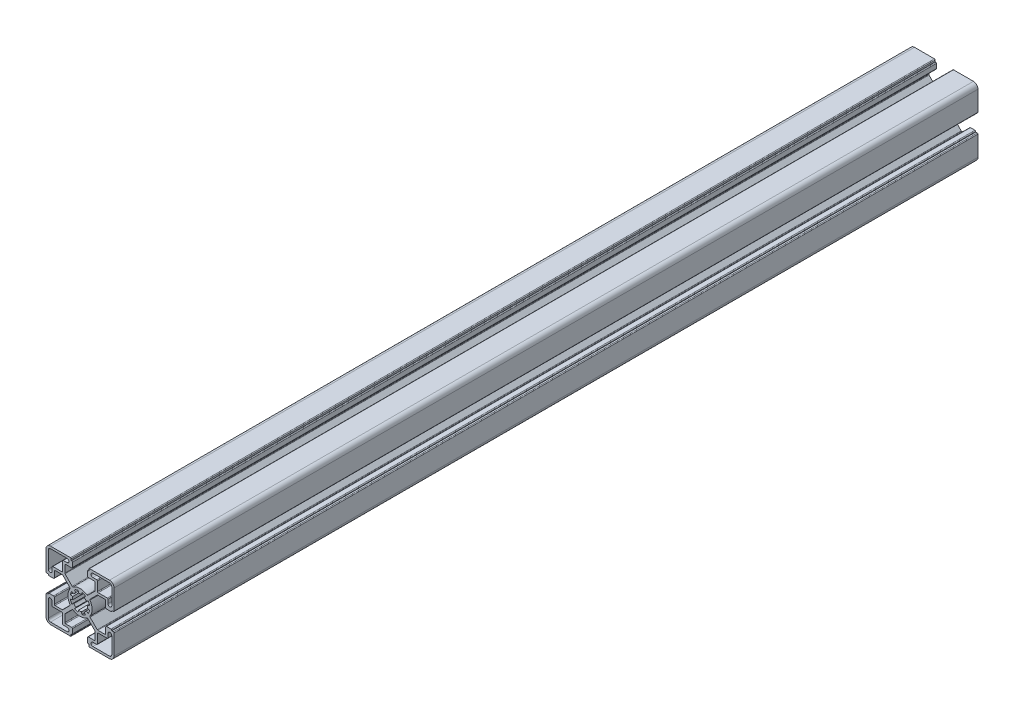
SolidWorks part; units mm, degrees
material "6063-O"
ref_plane "Front Plane" through (0, 0, 0) normal (0, 0, 1) x (1, 0, 0)
ref_plane "Top Plane" through (0, 0, 0) normal (0, 1, 0) x (1, 0, 0)
ref_plane "Right Plane" through (0, 0, 0) normal (1, 0, 0) x (0, 0, -1)
sketch "Sketch1" plane through (0, 0, 0) normal (0, 0, 1) x (1, 0, 0)
  line L0 (0, 22.5) -> (0, -22.5) construction
  line L1 (22.5, 0) -> (-22.5, 0) construction
  line L2 (-5.8, 22.5) -> (5.8, 22.5) construction
  line L3 (-5, 21) -> (5, 21) construction
  line L4 (-10.05, 10.05) -> (10.05, 10.05) construction
  line L5 (0, 0) -> (-10.05, 10.05) construction
  circle A0 centre (0, 0) radius 5 construction
  point P4 (0, 0)
  point P8 (0, 0)
  point P10 (0, 8)
  point P14 (0, 22.5)
  point P17 (0, 21)
  point P19 (0, 10.05)
sketch "Sketch2" plane through (0, 0, 0) normal (1, 0, 0) x (0, 0, -1)
  line L0 (152.4, 0) -> (-152.4, 0) construction
  point P4 (0, 0)
  dimension "D1" = 304.8
sketch "Sketch3" plane through (0, 0, 0) normal (0, 0, 1) x (1, 0, 0)
  line L5 (-21, 8.5375) -> (-21, 19.5)
  line L9 (0, 0) -> (-22.5, 22.5) construction
  line L10 (-11.55, -10.05) -> (-6.3569, -4.8569)
  line L11 (-19.5, 21) -> (-8.5375, 21)
  line L38 (-5.8, 22.5) -> (-5.8, 21)
  line L46 (-5.8, 21) -> (-5, 21)
  line L62 (-5, 21) -> (-5, 17.025)
  line L74 (-5, 17.025) -> (-10.05, 17.025)
  line L76 (-10.05, 17.025) -> (-10.05, 11.55)
  line L77 (-10.05, 11.55) -> (-4.8569, 6.3569)
  line L78 (-18.525, 8.5375) -> (-18.525, 11.55)
  line L79 (-10.05, 17.025) -> (-10.05, 22.5) construction
  line L80 (0, 22.5) -> (0, -22.5) construction
  line L81 (-5.8, 22.5) -> (5.8, 22.5) construction
  line L82 (10.05, 11.55) -> (4.8569, 6.3569)
  line L83 (10.05, 17.025) -> (10.05, 11.55)
  line L84 (5, 17.025) -> (10.05, 17.025)
  line L85 (5, 21) -> (5, 17.025)
  line L86 (5.8, 21) -> (5, 21)
  line L87 (5.8, 22.5) -> (5.8, 21)
  line L88 (-22.5, -5.8) -> (-21, -5.8)
  line L89 (-21, -5.8) -> (-21, -5)
  line L90 (-21, -5) -> (-17.025, -5)
  line L91 (-17.025, -5) -> (-17.025, -10.05)
  line L92 (-17.025, -10.05) -> (-11.55, -10.05)
  line L93 (-11.55, -10.05) -> (-6.3569, -4.8569)
  line L94 (-11.55, 10.05) -> (-6.3569, 4.8569)
  line L95 (-17.025, 10.05) -> (-11.55, 10.05)
  line L96 (-17.025, 5) -> (-17.025, 10.05)
  line L97 (-21, 5) -> (-17.025, 5)
  line L98 (-21, 5.8) -> (-21, 5)
  line L99 (-22.5, 5.8) -> (-21, 5.8)
  line L100 (-22.5, 5.8) -> (-22.5, 19.5)
  line L101 (-19.5, 22.5) -> (-5.8, 22.5)
  line L102 (-18.525, 11.55) -> (-11.55, 11.55)
  line L103 (-8.5375, 18.525) -> (-11.55, 18.525)
  line L104 (-11.55, 18.525) -> (-11.55, 11.55)
  line L108 (5.8, -22.5) -> (5.8, -21)
  line L113 (5.8, -21) -> (5, -21)
  line L117 (5.8, 22.5) -> (19.5, 22.5)
  line L118 (22.5, 19.5) -> (22.5, 5.8)
  line L119 (19.5, -22.5) -> (5.8, -22.5)
  line L120 (0, 0) -> (22.5, 0) construction
  line L121 (-22.5, -19.5) -> (-22.5, -5.8)
  line L136 (5, -21) -> (5, -17.025)
  line L137 (5, -17.025) -> (10.05, -17.025)
  line L138 (10.05, -17.025) -> (10.05, -11.55)
  line L139 (10.05, -11.55) -> (4.8569, -6.3569)
  line L140 (-10.05, -11.55) -> (-4.8569, -6.3569)
  line L141 (-10.05, -17.025) -> (-10.05, -11.55)
  line L142 (-5, -17.025) -> (-10.05, -17.025)
  line L143 (-5, -21) -> (-5, -17.025)
  line L144 (-5.8, -21) -> (-5, -21)
  line L145 (-5.8, -22.5) -> (-5.8, -21)
  line L146 (-5.8, -22.5) -> (-19.5, -22.5)
  line L147 (22.5, 5.8) -> (21, 5.8)
  line L148 (21, 5.8) -> (21, 5)
  line L149 (21, 5) -> (17.025, 5)
  line L150 (17.025, 5) -> (17.025, 10.05)
  line L151 (17.025, 10.05) -> (11.55, 10.05)
  line L152 (11.55, 10.05) -> (6.3569, 4.8569)
  line L153 (11.55, -10.05) -> (6.3569, -4.8569)
  line L154 (17.025, -10.05) -> (11.55, -10.05)
  line L155 (17.025, -5) -> (17.025, -10.05)
  line L156 (21, -5) -> (17.025, -5)
  line L157 (21, -5.8) -> (21, -5)
  line L158 (22.5, -5.8) -> (21, -5.8)
  line L159 (11.55, -10.05) -> (6.3569, -4.8569)
  line L160 (22.5, -5.8) -> (22.5, -19.5)
  line L161 (8.5375, 21) -> (19.5, 21)
  line L162 (21, 19.5) -> (21, 8.5375)
  line L163 (8.5375, 18.525) -> (11.55, 18.525)
  line L164 (11.55, 18.525) -> (11.55, 11.55)
  line L165 (18.525, 8.5375) -> (18.525, 11.55)
  line L166 (18.525, 11.55) -> (11.55, 11.55)
  line L167 (21, -8.5375) -> (21, -19.5)
  line L168 (19.5, -21) -> (8.5375, -21)
  line L169 (18.525, -8.5375) -> (18.525, -11.55)
  line L170 (18.525, -11.55) -> (11.55, -11.55)
  line L171 (8.5375, -18.525) -> (11.55, -18.525)
  line L172 (11.55, -18.525) -> (11.55, -11.55)
  line L173 (-8.5375, -21) -> (-19.5, -21)
  line L174 (-21, -19.5) -> (-21, -8.5375)
  line L175 (-8.5375, -18.525) -> (-11.55, -18.525)
  line L176 (-11.55, -18.525) -> (-11.55, -11.55)
  line L177 (-18.525, -8.5375) -> (-18.525, -11.55)
  line L178 (-18.525, -11.55) -> (-11.55, -11.55)
  line L179 (0, 0) -> (-11.55, 11.55) construction
  line L180 (0, 0) -> (11.55, 11.55) construction
  arc A2 (-21, 19.5) -> (-19.5, 21) centre (-19.5, 19.5) cw
  arc A73 (-4.8569, 6.3569) -> (4.8569, 6.3569) centre (0, 0) cw
  arc A74 (-6.3569, 4.8569) -> (-6.3569, -4.8569) centre (0, 0) ccw
  arc A75 (-19.5, 22.5) -> (-22.5, 19.5) centre (-19.5, 19.5) ccw
  arc A76 (-21, 8.5375) -> (-18.525, 8.5375) centre (-19.7625, 8.5375) ccw
  arc A77 (-8.5375, 21) -> (-8.5375, 18.525) centre (-8.5375, 19.7625) cw
  arc A80 (19.5, 22.5) -> (22.5, 19.5) centre (19.5, 19.5) cw
  arc A81 (22.5, -19.5) -> (19.5, -22.5) centre (19.5, -19.5) cw
  arc A82 (-19.5, -22.5) -> (-22.5, -19.5) centre (-19.5, -19.5) cw
  circle A88 centre (0, 0) radius 5 construction
  circle A89 centre (0, 0) radius 5
  arc A90 (-4.8569, -6.3569) -> (4.8569, -6.3569) centre (0, 0) ccw
  arc A91 (19.5, 21) -> (21, 19.5) centre (19.5, 19.5) cw
  arc A92 (6.3569, 4.8569) -> (6.3569, -4.8569) centre (0, 0) cw
  arc A93 (8.5375, 21) -> (8.5375, 18.525) centre (8.5375, 19.7625) ccw
  arc A94 (21, 8.5375) -> (18.525, 8.5375) centre (19.7625, 8.5375) cw
  arc A95 (21, -19.5) -> (19.5, -21) centre (19.5, -19.5) cw
  arc A96 (21, -8.5375) -> (18.525, -8.5375) centre (19.7625, -8.5375) ccw
  arc A97 (8.5375, -21) -> (8.5375, -18.525) centre (8.5375, -19.7625) cw
  arc A98 (-19.5, -21) -> (-21, -19.5) centre (-19.5, -19.5) cw
  arc A99 (-8.5375, -21) -> (-8.5375, -18.525) centre (-8.5375, -19.7625) ccw
  arc A100 (-21, -8.5375) -> (-18.525, -8.5375) centre (-19.7625, -8.5375) cw
  point P54 (-14.2875, 10.05)
  dimension "D2" = 3
  dimension "D3" = 1.5
  dimension "D4" = 1.5
  dimension "D5" = 1.5
  dimension "D6" = 90
  dimension "D1" = 4
extrude "Boss-Extrude1" add sketch "Sketch3" along normal up to vertex (152.4 mm away) and the other way up to vertex (152.4 mm away) contours A92 L152 L151 L150 L149 L148 L147 L118 A80 L117 L87 L86 L85 L84 L83 L82 A73 L77 L76 L74 L62 L46 L38 L101 A75 L100 L99 L98 L97 L96 L95 L94 A74 L10 L92 L91 L90 L89 L88 L121 A82 L146 L145 L144 L143 L142 L141 L140 A90 L139 L138 up to point (0, 0, 152.4) other way up to point (0, 0, -152.4)
fillet "Fillet1" radius 0.5 58 edges at (5, 21, 0) (5.8, 22.5, 0) (-5.8, 22.5, 0) (-5, 21, 0) (-10.05, 17.025, 0) (-5, 17.025, 0) (5, 17.025, 0) (-22.5, -5.8, 0) (-21, -5, 0) (-17.025, -5, 0) (-17.025, -10.05, 0) (-11.55, -10.05, 0) (-6.3569, -4.8569, 0) (-6.3569, 4.8569, 0) (-11.55, 10.05, 0) (-17.025, 10.05, 0) (-17.025, 5, 0) (-22.5, 5.8, 0) (-21, 5, 0) (-18.525, 11.55, 0) (-11.55, 11.55, 0) (-11.55, 18.525, 0) (4.8569, 6.3569, 0) (-4.8569, 6.3569, 0) (-10.05, 11.55, 0) (10.05, 17.025, 0) (10.05, 11.55, 0) (22.5, -5.8, 0) (21, -5, 0) (17.025, -5, 0) (17.025, -10.05, 0) (6.3569, 4.8569, 0) (11.55, 10.05, 0) (22.5, 5.8, 0) (21, 5, 0) (17.025, 5, 0) (4.8569, -6.3569, 0) (11.55, -11.55, 0) (-11.55, -11.55, 0) (18.525, -11.55, 0) (11.55, -18.525, 0) (10.05, -17.025, 0) (5, -17.025, 0) (5, -21, 0) (5.8, -22.5, 0) (-5.8, -22.5, 0) (-5, -21, 0) (-5, -17.025, 0) (-10.05, -17.025, 0) (-11.55, -18.525, 0) (11.55, 18.525, 0) (18.525, 11.55, 0) (11.55, 11.55, 0) (11.55, -10.05, 0) (6.3569, -4.8569, 0) (-4.8569, -6.3569, 0) (10.05, -11.55, 0) (-10.05, -11.55, 0)
sketch "Sketch4" plane through (0, 0, 152.4) normal (0, 0, 1) x (1, 0, 0)
  line L0 (-1.2681, 6.3751) -> (-0.9755, 4.9039)
  line L1 (0, 0) -> (0, 8) construction
  line L2 (-3.6112, 5.4046) -> (-2.7779, 4.1573)
  line L3 (1.2681, 6.3751) -> (0.9755, 4.9039)
  line L4 (3.6112, 5.4046) -> (2.7779, 4.1573)
  line L5 (5.4046, 3.6112) -> (4.1573, 2.7779)
  line L6 (6.3751, 1.2681) -> (4.9039, 0.9755)
  line L7 (6.3751, -1.2681) -> (4.9039, -0.9755)
  line L8 (5.4046, -3.6112) -> (4.1573, -2.7779)
  line L9 (3.6112, -5.4046) -> (2.7779, -4.1573)
  line L10 (1.2681, -6.3751) -> (0.9755, -4.9039)
  line L11 (-1.2681, -6.3751) -> (-0.9755, -4.9039)
  line L12 (-3.6112, -5.4046) -> (-2.7779, -4.1573)
  line L13 (-5.4046, -3.6112) -> (-4.1573, -2.7779)
  line L14 (-6.3751, -1.2681) -> (-4.9039, -0.9755)
  line L15 (-6.3751, 1.2681) -> (-4.9039, 0.9755)
  line L16 (-5.4046, 3.6112) -> (-4.1573, 2.7779)
  line L17 (0, 0) -> (-0.9755, 4.9039) construction
  line L18 (0, 0) -> (2.7779, 4.1573) construction
  arc A0 (-1.2681, 6.3751) -> (-3.6112, 5.4046) centre (0, 0) ccw
  circle A1 centre (0, 0) radius 5 construction
  arc A2 (-0.9755, 4.9039) -> (-2.7779, 4.1573) centre (0, 0) ccw
  arc A4 (2.7779, 4.1573) -> (0.9755, 4.9039) centre (0, 0) ccw
  arc A5 (3.6112, 5.4046) -> (1.2681, 6.3751) centre (0, 0) ccw
  arc A6 (4.9039, 0.9755) -> (4.1573, 2.7779) centre (0, 0) ccw
  arc A7 (6.3751, 1.2681) -> (5.4046, 3.6112) centre (0, 0) ccw
  arc A8 (4.1573, -2.7779) -> (4.9039, -0.9755) centre (0, 0) ccw
  arc A9 (5.4046, -3.6112) -> (6.3751, -1.2681) centre (0, 0) ccw
  arc A10 (0.9755, -4.9039) -> (2.7779, -4.1573) centre (0, 0) ccw
  arc A11 (1.2681, -6.3751) -> (3.6112, -5.4046) centre (0, 0) ccw
  arc A12 (-2.7779, -4.1573) -> (-0.9755, -4.9039) centre (0, 0) ccw
  arc A13 (-3.6112, -5.4046) -> (-1.2681, -6.3751) centre (0, 0) ccw
  arc A14 (-4.9039, -0.9755) -> (-4.1573, -2.7779) centre (0, 0) ccw
  arc A15 (-6.3751, -1.2681) -> (-5.4046, -3.6112) centre (0, 0) ccw
  arc A16 (-4.1573, 2.7779) -> (-4.9039, 0.9755) centre (0, 0) ccw
  arc A17 (-5.4046, 3.6112) -> (-6.3751, 1.2681) centre (0, 0) ccw
  dimension "D1" = 1.5
  dimension "D2" = 22.5
  dimension "D5" = 45
  dimension "D4" = 8
extrude "Cut-Extrude1" cut sketch "Sketch4" against normal through all
sketch "Sketch5" plane through (0, 0, 152.4) normal (0, 0, 1) x (1, 0, 0)
  line L6 (-11.55, -18.025) -> (-11.55, -12.05)
  line L7 (-8.5375, -18.525) -> (-11.05, -18.525)
  line L8 (-19.5, -21) -> (-8.5375, -21)
  line L9 (-21, -8.5375) -> (-21, -19.5)
  line L10 (-18.525, -11.55) -> (-18.525, -8.5375)
  line L11 (-12.05, -11.55) -> (-18.525, -11.55)
  line L12 (-11.55, -18.025) -> (-11.55, -12.05)
  line L13 (-8.5375, -18.525) -> (-11.05, -18.525)
  line L14 (-19.5, -21) -> (-8.5375, -21)
  line L15 (-21, -8.5375) -> (-21, -19.5)
  line L16 (-0.9755, 4.9039) -> (-1.2681, 6.3751)
  line L17 (1.2681, 6.3751) -> (0.9755, 4.9039)
  line L18 (2.7779, 4.1573) -> (3.6112, 5.4046)
  line L19 (5.4046, 3.6112) -> (4.1573, 2.7779)
  line L20 (4.9039, 0.9755) -> (6.3751, 1.2681)
  line L21 (6.3751, -1.2681) -> (4.9039, -0.9755)
  line L22 (4.1573, -2.7779) -> (5.4046, -3.6112)
  line L23 (3.6112, -5.4046) -> (2.7779, -4.1573)
  line L24 (0.9755, -4.9039) -> (1.2681, -6.3751)
  line L25 (-1.2681, -6.3751) -> (-0.9755, -4.9039)
  line L26 (-2.7779, -4.1573) -> (-3.6112, -5.4046)
  line L27 (-5.4046, -3.6112) -> (-4.1573, -2.7779)
  line L28 (-4.9039, -0.9755) -> (-6.3751, -1.2681)
  line L29 (-6.3751, 1.2681) -> (-4.9039, 0.9755)
  line L30 (-4.1573, 2.7779) -> (-5.4046, 3.6112)
  line L31 (-3.6112, 5.4046) -> (-2.7779, 4.1573)
  line L32 (-0.9755, 4.9039) -> (-1.2681, 6.3751)
  line L33 (1.2681, 6.3751) -> (0.9755, 4.9039)
  line L34 (2.7779, 4.1573) -> (3.6112, 5.4046)
  line L35 (5.4046, 3.6112) -> (4.1573, 2.7779)
  line L36 (4.9039, 0.9755) -> (6.3751, 1.2681)
  line L37 (6.3751, -1.2681) -> (4.9039, -0.9755)
  line L38 (4.1573, -2.7779) -> (5.4046, -3.6112)
  line L39 (3.6112, -5.4046) -> (2.7779, -4.1573)
  line L40 (0.9755, -4.9039) -> (1.2681, -6.3751)
  line L41 (-1.2681, -6.3751) -> (-0.9755, -4.9039)
  line L42 (-2.7779, -4.1573) -> (-3.6112, -5.4046)
  line L43 (-5.4046, -3.6112) -> (-4.1573, -2.7779)
  line L44 (-4.9039, -0.9755) -> (-6.3751, -1.2681)
  line L45 (-6.3751, 1.2681) -> (-4.9039, 0.9755)
  line L46 (-4.1573, 2.7779) -> (-5.4046, 3.6112)
  line L47 (-3.6112, 5.4046) -> (-2.7779, 4.1573)
  line L48 (-18.525, -11.55) -> (-18.525, -8.5375)
  line L49 (-12.05, -11.55) -> (-18.525, -11.55)
  line L50 (18.025, -11.55) -> (12.05, -11.55)
  line L51 (18.525, -8.5375) -> (18.525, -11.05)
  line L52 (21, -19.5) -> (21, -8.5375)
  line L53 (8.5375, -21) -> (19.5, -21)
  line L54 (11.05, -18.525) -> (8.5375, -18.525)
  line L55 (11.55, -12.05) -> (11.55, -18.025)
  line L56 (22.5, -19.5) -> (22.5, -6.3)
  line L57 (22, -5.8) -> (21, -5.8)
  line L58 (21, -5.8) -> (21, -5.5)
  line L59 (20.5, -5) -> (17.525, -5)
  line L60 (17.025, -5.5) -> (17.025, -9.55)
  line L61 (16.525, -10.05) -> (11.7571, -10.05)
  line L62 (11.4036, -9.9036) -> (6.6582, -5.1582)
  line L63 (6.6582, 5.1582) -> (11.4036, 9.9036)
  line L64 (11.7571, 10.05) -> (17.025, 10.05)
  line L65 (17.025, 10.05) -> (17.025, 5.5)
  line L66 (17.525, 5) -> (20.5, 5)
  line L67 (21, 5.5) -> (21, 5.8)
  line L68 (21, 5.8) -> (22, 5.8)
  line L69 (22.5, 6.3) -> (22.5, 19.5)
  line L70 (19.5, 22.5) -> (6.3, 22.5)
  line L71 (5.8, 22) -> (5.8, 21)
  line L72 (5.8, 21) -> (5.5, 21)
  line L73 (5, 20.5) -> (5, 17.525)
  line L74 (5.5, 17.025) -> (9.55, 17.025)
  line L75 (10.05, 16.525) -> (10.05, 11.7571)
  line L76 (9.9036, 11.4036) -> (5.1582, 6.6582)
  line L77 (-5.1582, 6.6582) -> (-9.9036, 11.4036)
  line L78 (-10.05, 11.7571) -> (-10.05, 16.525)
  line L79 (-9.55, 17.025) -> (-5.5, 17.025)
  line L80 (-5, 17.525) -> (-5, 20.5)
  line L81 (-5.5, 21) -> (-5.8, 21)
  line L82 (-5.8, 21) -> (-5.8, 22)
  line L83 (-6.3, 22.5) -> (-19.5, 22.5)
  line L84 (-22.5, 19.5) -> (-22.5, 6.3)
  line L85 (-22, 5.8) -> (-21, 5.8)
  line L86 (-21, 5.8) -> (-21, 5.5)
  line L87 (-20.5, 5) -> (-17.525, 5)
  line L88 (-17.025, 5.5) -> (-17.025, 9.55)
  line L89 (-16.525, 10.05) -> (-11.7571, 10.05)
  line L90 (-11.4036, 9.9036) -> (-6.6582, 5.1582)
  line L91 (-6.6582, -5.1582) -> (-11.4036, -9.9036)
  line L92 (-11.7571, -10.05) -> (-16.525, -10.05)
  line L93 (-17.025, -9.55) -> (-17.025, -5.5)
  line L94 (-17.525, -5) -> (-20.5, -5)
  line L95 (-21, -5.5) -> (-21, -5.8)
  line L96 (-21, -5.8) -> (-22, -5.8)
  line L97 (-22.5, -6.3) -> (-22.5, -19.5)
  line L98 (-19.5, -22.5) -> (-6.3, -22.5)
  line L99 (-5.8, -22) -> (-5.8, -21)
  line L100 (-5.8, -21) -> (-5.5, -21)
  line L101 (-5, -20.5) -> (-5, -17.525)
  line L102 (-5.5, -17.025) -> (-9.55, -17.025)
  line L103 (-10.05, -16.525) -> (-10.05, -11.7571)
  line L104 (-9.9036, -11.4036) -> (-5.1582, -6.6582)
  line L105 (5.1582, -6.6582) -> (9.9036, -11.4036)
  line L106 (10.05, -11.7571) -> (10.05, -16.525)
  line L107 (9.55, -17.025) -> (5.5, -17.025)
  line L108 (5, -17.525) -> (5, -20.5)
  line L109 (5.5, -21) -> (5.8, -21)
  line L110 (5.8, -21) -> (5.8, -22)
  line L111 (6.3, -22.5) -> (19.5, -22.5)
  line L112 (22.5, -19.5) -> (22.5, -6.3)
  line L113 (22, -5.8) -> (21, -5.8)
  line L114 (21, -5.8) -> (21, -5.5)
  line L115 (20.5, -5) -> (17.525, -5)
  line L116 (17.025, -5.5) -> (17.025, -9.55)
  line L117 (16.525, -10.05) -> (11.7571, -10.05)
  line L118 (11.4036, -9.9036) -> (6.6582, -5.1582)
  line L119 (6.6582, 5.1582) -> (11.4036, 9.9036)
  line L120 (11.7571, 10.05) -> (17.025, 10.05)
  line L121 (17.025, 10.05) -> (17.025, 5.5)
  line L122 (17.525, 5) -> (20.5, 5)
  line L123 (21, 5.5) -> (21, 5.8)
  line L124 (21, 5.8) -> (22, 5.8)
  line L125 (22.5, 6.3) -> (22.5, 19.5)
  line L126 (19.5, 22.5) -> (6.3, 22.5)
  line L127 (5.8, 22) -> (5.8, 21)
  line L128 (5.8, 21) -> (5.5, 21)
  line L129 (5, 20.5) -> (5, 17.525)
  line L130 (5.5, 17.025) -> (9.55, 17.025)
  line L131 (10.05, 16.525) -> (10.05, 11.7571)
  line L132 (9.9036, 11.4036) -> (5.1582, 6.6582)
  line L133 (-5.1582, 6.6582) -> (-9.9036, 11.4036)
  line L134 (-10.05, 11.7571) -> (-10.05, 16.525)
  line L135 (-9.55, 17.025) -> (-5.5, 17.025)
  line L136 (-5, 17.525) -> (-5, 20.5)
  line L137 (-5.5, 21) -> (-5.8, 21)
  line L138 (-5.8, 21) -> (-5.8, 22)
  line L139 (-6.3, 22.5) -> (-19.5, 22.5)
  line L140 (-22.5, 19.5) -> (-22.5, 6.3)
  line L141 (-22, 5.8) -> (-21, 5.8)
  line L142 (-21, 5.8) -> (-21, 5.5)
  line L143 (-20.5, 5) -> (-17.525, 5)
  line L144 (-17.025, 5.5) -> (-17.025, 9.55)
  line L145 (-16.525, 10.05) -> (-11.7571, 10.05)
  line L146 (-11.4036, 9.9036) -> (-6.6582, 5.1582)
  line L147 (-6.6582, -5.1582) -> (-11.4036, -9.9036)
  line L148 (-11.7571, -10.05) -> (-16.525, -10.05)
  line L149 (-17.025, -9.55) -> (-17.025, -5.5)
  line L150 (-17.525, -5) -> (-20.5, -5)
  line L151 (-21, -5.5) -> (-21, -5.8)
  line L152 (-21, -5.8) -> (-22, -5.8)
  line L153 (-22.5, -6.3) -> (-22.5, -19.5)
  line L154 (-19.5, -22.5) -> (-6.3, -22.5)
  line L155 (-5.8, -22) -> (-5.8, -21)
  line L156 (-5.8, -21) -> (-5.5, -21)
  line L157 (-5, -20.5) -> (-5, -17.525)
  line L158 (-5.5, -17.025) -> (-9.55, -17.025)
  line L159 (-10.05, -16.525) -> (-10.05, -11.7571)
  line L160 (-9.9036, -11.4036) -> (-5.1582, -6.6582)
  line L161 (5.1582, -6.6582) -> (9.9036, -11.4036)
  line L162 (10.05, -11.7571) -> (10.05, -16.525)
  line L163 (9.55, -17.025) -> (5.5, -17.025)
  line L164 (5, -17.525) -> (5, -20.5)
  line L165 (5.5, -21) -> (5.8, -21)
  line L166 (5.8, -21) -> (5.8, -22)
  line L167 (6.3, -22.5) -> (19.5, -22.5)
  line L168 (18.025, -11.55) -> (12.05, -11.55)
  line L169 (18.525, -8.5375) -> (18.525, -11.05)
  line L170 (21, -19.5) -> (21, -8.5375)
  line L171 (8.5375, -21) -> (19.5, -21)
  line L172 (11.05, -18.525) -> (8.5375, -18.525)
  line L173 (11.55, -12.05) -> (11.55, -18.025)
  line L174 (11.55, 18.025) -> (11.55, 12.05)
  line L175 (8.5375, 18.525) -> (11.05, 18.525)
  line L176 (19.5, 21) -> (8.5375, 21)
  line L177 (21, 8.5375) -> (21, 19.5)
  line L178 (18.525, 11.05) -> (18.525, 8.5375)
  line L179 (12.05, 11.55) -> (18.025, 11.55)
  line L180 (11.55, 18.025) -> (11.55, 12.05)
  line L181 (8.5375, 18.525) -> (11.05, 18.525)
  line L182 (19.5, 21) -> (8.5375, 21)
  line L183 (21, 8.5375) -> (21, 19.5)
  line L184 (18.525, 11.05) -> (18.525, 8.5375)
  line L185 (12.05, 11.55) -> (18.025, 11.55)
  line L186 (-18.025, 11.55) -> (-12.05, 11.55)
  line L187 (-18.525, 8.5375) -> (-18.525, 11.05)
  line L188 (-21, 19.5) -> (-21, 8.5375)
  line L189 (-8.5375, 21) -> (-19.5, 21)
  line L190 (-11.05, 18.525) -> (-8.5375, 18.525)
  line L191 (-11.55, 12.05) -> (-11.55, 18.025)
  line L192 (-18.025, 11.55) -> (-12.05, 11.55)
  line L193 (-18.525, 8.5375) -> (-18.525, 11.05)
  line L194 (-21, 19.5) -> (-21, 8.5375)
  line L195 (-8.5375, 21) -> (-19.5, 21)
  line L196 (-11.05, 18.525) -> (-8.5375, 18.525)
  line L197 (-11.55, 12.05) -> (-11.55, 18.025)
  arc A5 (-11.55, -18.025) -> (-11.05, -18.525) centre (-11.05, -18.025) ccw
  arc A6 (-8.5375, -21) -> (-8.5375, -18.525) centre (-8.5375, -19.7625) ccw
  arc A7 (-21, -19.5) -> (-19.5, -21) centre (-19.5, -19.5) ccw
  arc A8 (-18.525, -8.5375) -> (-21, -8.5375) centre (-19.7625, -8.5375) ccw
  arc A9 (-11.55, -12.05) -> (-12.05, -11.55) centre (-12.05, -12.05) ccw
  arc A10 (-11.55, -18.025) -> (-11.05, -18.525) centre (-11.05, -18.025) ccw
  arc A11 (-8.5375, -21) -> (-8.5375, -18.525) centre (-8.5375, -19.7625) ccw
  arc A12 (-21, -19.5) -> (-19.5, -21) centre (-19.5, -19.5) ccw
  arc A13 (-18.525, -8.5375) -> (-21, -8.5375) centre (-19.7625, -8.5375) ccw
  arc A14 (-11.55, -12.05) -> (-12.05, -11.55) centre (-12.05, -12.05) ccw
  arc A16 (0.9755, 4.9039) -> (-0.9755, 4.9039) centre (0, 0) ccw
  arc A17 (3.6112, 5.4046) -> (1.2681, 6.3751) centre (0, 0) ccw
  arc A18 (4.1573, 2.7779) -> (2.7779, 4.1573) centre (0, 0) ccw
  arc A19 (6.3751, 1.2681) -> (5.4046, 3.6112) centre (0, 0) ccw
  arc A20 (4.9039, -0.9755) -> (4.9039, 0.9755) centre (0, 0) ccw
  arc A21 (5.4046, -3.6112) -> (6.3751, -1.2681) centre (0, 0) ccw
  arc A22 (2.7779, -4.1573) -> (4.1573, -2.7779) centre (0, 0) ccw
  arc A23 (1.2681, -6.3751) -> (3.6112, -5.4046) centre (0, 0) ccw
  arc A24 (-0.9755, -4.9039) -> (0.9755, -4.9039) centre (0, 0) ccw
  arc A25 (-3.6112, -5.4046) -> (-1.2681, -6.3751) centre (0, 0) ccw
  arc A26 (-4.1573, -2.7779) -> (-2.7779, -4.1573) centre (0, 0) ccw
  arc A27 (-6.3751, -1.2681) -> (-5.4046, -3.6112) centre (0, 0) ccw
  arc A28 (-4.9039, 0.9755) -> (-4.9039, -0.9755) centre (0, 0) ccw
  arc A29 (-5.4046, 3.6112) -> (-6.3751, 1.2681) centre (0, 0) ccw
  arc A30 (-2.7779, 4.1573) -> (-4.1573, 2.7779) centre (0, 0) ccw
  arc A31 (-1.2681, 6.3751) -> (-3.6112, 5.4046) centre (0, 0) ccw
  arc A32 (0.9755, 4.9039) -> (-0.9755, 4.9039) centre (0, 0) ccw
  arc A33 (3.6112, 5.4046) -> (1.2681, 6.3751) centre (0, 0) ccw
  arc A34 (4.1573, 2.7779) -> (2.7779, 4.1573) centre (0, 0) ccw
  arc A35 (6.3751, 1.2681) -> (5.4046, 3.6112) centre (0, 0) ccw
  arc A36 (4.9039, -0.9755) -> (4.9039, 0.9755) centre (0, 0) ccw
  arc A37 (5.4046, -3.6112) -> (6.3751, -1.2681) centre (0, 0) ccw
  arc A38 (2.7779, -4.1573) -> (4.1573, -2.7779) centre (0, 0) ccw
  arc A39 (1.2681, -6.3751) -> (3.6112, -5.4046) centre (0, 0) ccw
  arc A40 (-0.9755, -4.9039) -> (0.9755, -4.9039) centre (0, 0) ccw
  arc A41 (-3.6112, -5.4046) -> (-1.2681, -6.3751) centre (0, 0) ccw
  arc A42 (-4.1573, -2.7779) -> (-2.7779, -4.1573) centre (0, 0) ccw
  arc A43 (-6.3751, -1.2681) -> (-5.4046, -3.6112) centre (0, 0) ccw
  arc A44 (-4.9039, 0.9755) -> (-4.9039, -0.9755) centre (0, 0) ccw
  arc A45 (-5.4046, 3.6112) -> (-6.3751, 1.2681) centre (0, 0) ccw
  arc A46 (-2.7779, 4.1573) -> (-4.1573, 2.7779) centre (0, 0) ccw
  arc A47 (-1.2681, 6.3751) -> (-3.6112, 5.4046) centre (0, 0) ccw
  arc A48 (18.025, -11.55) -> (18.525, -11.05) centre (18.025, -11.05) ccw
  arc A49 (21, -8.5375) -> (18.525, -8.5375) centre (19.7625, -8.5375) ccw
  arc A50 (19.5, -21) -> (21, -19.5) centre (19.5, -19.5) ccw
  arc A51 (8.5375, -18.525) -> (8.5375, -21) centre (8.5375, -19.7625) ccw
  arc A52 (11.05, -18.525) -> (11.55, -18.025) centre (11.05, -18.025) ccw
  arc A53 (12.05, -11.55) -> (11.55, -12.05) centre (12.05, -12.05) ccw
  arc A54 (18.025, -11.55) -> (18.525, -11.05) centre (18.025, -11.05) ccw
  arc A55 (22.5, -6.3) -> (22, -5.8) centre (22, -6.3) ccw
  arc A56 (21, -5.5) -> (20.5, -5) centre (20.5, -5.5) ccw
  arc A57 (17.525, -5) -> (17.025, -5.5) centre (17.525, -5.5) ccw
  arc A58 (16.525, -10.05) -> (17.025, -9.55) centre (16.525, -9.55) ccw
  arc A59 (11.4036, -9.9036) -> (11.7571, -10.05) centre (11.7571, -9.55) ccw
  arc A60 (6.5993, -4.522) -> (6.6582, -5.1582) centre (7.0118, -4.8047) ccw
  arc A61 (6.5993, -4.522) -> (6.5993, 4.522) centre (0, 0) ccw
  arc A62 (6.6582, 5.1582) -> (6.5993, 4.522) centre (7.0118, 4.8047) ccw
  arc A63 (11.7571, 10.05) -> (11.4036, 9.9036) centre (11.7571, 9.55) ccw
  arc A64 (17.025, 5.5) -> (17.525, 5) centre (17.525, 5.5) ccw
  arc A65 (20.5, 5) -> (21, 5.5) centre (20.5, 5.5) ccw
  arc A66 (22, 5.8) -> (22.5, 6.3) centre (22, 6.3) ccw
  arc A67 (22.5, 19.5) -> (19.5, 22.5) centre (19.5, 19.5) ccw
  arc A68 (6.3, 22.5) -> (5.8, 22) centre (6.3, 22) ccw
  arc A69 (5.5, 21) -> (5, 20.5) centre (5.5, 20.5) ccw
  arc A70 (5, 17.525) -> (5.5, 17.025) centre (5.5, 17.525) ccw
  arc A71 (10.05, 16.525) -> (9.55, 17.025) centre (9.55, 16.525) ccw
  arc A72 (9.9036, 11.4036) -> (10.05, 11.7571) centre (9.55, 11.7571) ccw
  arc A73 (4.522, 6.5993) -> (5.1582, 6.6582) centre (4.8047, 7.0118) ccw
  arc A74 (4.522, 6.5993) -> (-4.522, 6.5993) centre (0, 0) ccw
  arc A75 (-5.1582, 6.6582) -> (-4.522, 6.5993) centre (-4.8047, 7.0118) ccw
  arc A76 (-10.05, 11.7571) -> (-9.9036, 11.4036) centre (-9.55, 11.7571) ccw
  arc A77 (-9.55, 17.025) -> (-10.05, 16.525) centre (-9.55, 16.525) ccw
  arc A78 (-5.5, 17.025) -> (-5, 17.525) centre (-5.5, 17.525) ccw
  arc A79 (-5, 20.5) -> (-5.5, 21) centre (-5.5, 20.5) ccw
  arc A80 (-5.8, 22) -> (-6.3, 22.5) centre (-6.3, 22) ccw
  arc A81 (-19.5, 22.5) -> (-22.5, 19.5) centre (-19.5, 19.5) ccw
  arc A82 (-22.5, 6.3) -> (-22, 5.8) centre (-22, 6.3) ccw
  arc A83 (-21, 5.5) -> (-20.5, 5) centre (-20.5, 5.5) ccw
  arc A84 (-17.525, 5) -> (-17.025, 5.5) centre (-17.525, 5.5) ccw
  arc A85 (-16.525, 10.05) -> (-17.025, 9.55) centre (-16.525, 9.55) ccw
  arc A86 (-11.4036, 9.9036) -> (-11.7571, 10.05) centre (-11.7571, 9.55) ccw
  arc A87 (-6.5993, 4.522) -> (-6.6582, 5.1582) centre (-7.0118, 4.8047) ccw
  arc A88 (-6.5993, 4.522) -> (-6.5993, -4.522) centre (0, 0) ccw
  arc A89 (-6.6582, -5.1582) -> (-6.5993, -4.522) centre (-7.0118, -4.8047) ccw
  arc A90 (-11.7571, -10.05) -> (-11.4036, -9.9036) centre (-11.7571, -9.55) ccw
  arc A91 (-17.025, -9.55) -> (-16.525, -10.05) centre (-16.525, -9.55) ccw
  arc A92 (-17.025, -5.5) -> (-17.525, -5) centre (-17.525, -5.5) ccw
  arc A93 (-20.5, -5) -> (-21, -5.5) centre (-20.5, -5.5) ccw
  arc A94 (-22, -5.8) -> (-22.5, -6.3) centre (-22, -6.3) ccw
  arc A95 (-22.5, -19.5) -> (-19.5, -22.5) centre (-19.5, -19.5) ccw
  arc A96 (-6.3, -22.5) -> (-5.8, -22) centre (-6.3, -22) ccw
  arc A97 (-5.5, -21) -> (-5, -20.5) centre (-5.5, -20.5) ccw
  arc A98 (-5, -17.525) -> (-5.5, -17.025) centre (-5.5, -17.525) ccw
  arc A99 (-10.05, -16.525) -> (-9.55, -17.025) centre (-9.55, -16.525) ccw
  arc A100 (-9.9036, -11.4036) -> (-10.05, -11.7571) centre (-9.55, -11.7571) ccw
  arc A101 (-4.522, -6.5993) -> (-5.1582, -6.6582) centre (-4.8047, -7.0118) ccw
  arc A102 (-4.522, -6.5993) -> (4.522, -6.5993) centre (0, 0) ccw
  arc A103 (5.1582, -6.6582) -> (4.522, -6.5993) centre (4.8047, -7.0118) ccw
  arc A104 (10.05, -11.7571) -> (9.9036, -11.4036) centre (9.55, -11.7571) ccw
  arc A105 (9.55, -17.025) -> (10.05, -16.525) centre (9.55, -16.525) ccw
  arc A106 (5.5, -17.025) -> (5, -17.525) centre (5.5, -17.525) ccw
  arc A107 (5, -20.5) -> (5.5, -21) centre (5.5, -20.5) ccw
  arc A108 (5.8, -22) -> (6.3, -22.5) centre (6.3, -22) ccw
  arc A109 (19.5, -22.5) -> (22.5, -19.5) centre (19.5, -19.5) ccw
  arc A110 (22.5, -6.3) -> (22, -5.8) centre (22, -6.3) ccw
  arc A111 (21, -5.5) -> (20.5, -5) centre (20.5, -5.5) ccw
  arc A112 (17.525, -5) -> (17.025, -5.5) centre (17.525, -5.5) ccw
  arc A113 (16.525, -10.05) -> (17.025, -9.55) centre (16.525, -9.55) ccw
  arc A114 (11.4036, -9.9036) -> (11.7571, -10.05) centre (11.7571, -9.55) ccw
  arc A115 (6.5993, -4.522) -> (6.6582, -5.1582) centre (7.0118, -4.8047) ccw
  arc A116 (6.5993, -4.522) -> (6.5993, 4.522) centre (0, 0) ccw
  arc A117 (6.6582, 5.1582) -> (6.5993, 4.522) centre (7.0118, 4.8047) ccw
  arc A118 (11.7571, 10.05) -> (11.4036, 9.9036) centre (11.7571, 9.55) ccw
  arc A119 (17.025, 5.5) -> (17.525, 5) centre (17.525, 5.5) ccw
  arc A120 (20.5, 5) -> (21, 5.5) centre (20.5, 5.5) ccw
  arc A121 (22, 5.8) -> (22.5, 6.3) centre (22, 6.3) ccw
  arc A122 (22.5, 19.5) -> (19.5, 22.5) centre (19.5, 19.5) ccw
  arc A123 (6.3, 22.5) -> (5.8, 22) centre (6.3, 22) ccw
  arc A124 (5.5, 21) -> (5, 20.5) centre (5.5, 20.5) ccw
  arc A125 (5, 17.525) -> (5.5, 17.025) centre (5.5, 17.525) ccw
  arc A126 (10.05, 16.525) -> (9.55, 17.025) centre (9.55, 16.525) ccw
  arc A127 (9.9036, 11.4036) -> (10.05, 11.7571) centre (9.55, 11.7571) ccw
  arc A128 (4.522, 6.5993) -> (5.1582, 6.6582) centre (4.8047, 7.0118) ccw
  arc A129 (4.522, 6.5993) -> (-4.522, 6.5993) centre (0, 0) ccw
  arc A130 (-5.1582, 6.6582) -> (-4.522, 6.5993) centre (-4.8047, 7.0118) ccw
  arc A131 (-10.05, 11.7571) -> (-9.9036, 11.4036) centre (-9.55, 11.7571) ccw
  arc A132 (-9.55, 17.025) -> (-10.05, 16.525) centre (-9.55, 16.525) ccw
  arc A133 (-5.5, 17.025) -> (-5, 17.525) centre (-5.5, 17.525) ccw
  arc A134 (-5, 20.5) -> (-5.5, 21) centre (-5.5, 20.5) ccw
  arc A135 (-5.8, 22) -> (-6.3, 22.5) centre (-6.3, 22) ccw
  arc A136 (-19.5, 22.5) -> (-22.5, 19.5) centre (-19.5, 19.5) ccw
  arc A137 (-22.5, 6.3) -> (-22, 5.8) centre (-22, 6.3) ccw
  arc A138 (-21, 5.5) -> (-20.5, 5) centre (-20.5, 5.5) ccw
  arc A139 (-17.525, 5) -> (-17.025, 5.5) centre (-17.525, 5.5) ccw
  arc A140 (-16.525, 10.05) -> (-17.025, 9.55) centre (-16.525, 9.55) ccw
  arc A141 (-11.4036, 9.9036) -> (-11.7571, 10.05) centre (-11.7571, 9.55) ccw
  arc A142 (-6.5993, 4.522) -> (-6.6582, 5.1582) centre (-7.0118, 4.8047) ccw
  arc A143 (-6.5993, 4.522) -> (-6.5993, -4.522) centre (0, 0) ccw
  arc A144 (-6.6582, -5.1582) -> (-6.5993, -4.522) centre (-7.0118, -4.8047) ccw
  arc A145 (-11.7571, -10.05) -> (-11.4036, -9.9036) centre (-11.7571, -9.55) ccw
  arc A146 (-17.025, -9.55) -> (-16.525, -10.05) centre (-16.525, -9.55) ccw
  arc A147 (-17.025, -5.5) -> (-17.525, -5) centre (-17.525, -5.5) ccw
  arc A148 (-20.5, -5) -> (-21, -5.5) centre (-20.5, -5.5) ccw
  arc A149 (-22, -5.8) -> (-22.5, -6.3) centre (-22, -6.3) ccw
  arc A150 (-22.5, -19.5) -> (-19.5, -22.5) centre (-19.5, -19.5) ccw
  arc A151 (-6.3, -22.5) -> (-5.8, -22) centre (-6.3, -22) ccw
  arc A152 (-5.5, -21) -> (-5, -20.5) centre (-5.5, -20.5) ccw
  arc A153 (-5, -17.525) -> (-5.5, -17.025) centre (-5.5, -17.525) ccw
  arc A154 (-10.05, -16.525) -> (-9.55, -17.025) centre (-9.55, -16.525) ccw
  arc A155 (-9.9036, -11.4036) -> (-10.05, -11.7571) centre (-9.55, -11.7571) ccw
  arc A156 (-4.522, -6.5993) -> (-5.1582, -6.6582) centre (-4.8047, -7.0118) ccw
  arc A157 (-4.522, -6.5993) -> (4.522, -6.5993) centre (0, 0) ccw
  arc A158 (5.1582, -6.6582) -> (4.522, -6.5993) centre (4.8047, -7.0118) ccw
  arc A159 (10.05, -11.7571) -> (9.9036, -11.4036) centre (9.55, -11.7571) ccw
  arc A160 (9.55, -17.025) -> (10.05, -16.525) centre (9.55, -16.525) ccw
  arc A161 (5.5, -17.025) -> (5, -17.525) centre (5.5, -17.525) ccw
  arc A162 (5, -20.5) -> (5.5, -21) centre (5.5, -20.5) ccw
  arc A163 (5.8, -22) -> (6.3, -22.5) centre (6.3, -22) ccw
  arc A164 (19.5, -22.5) -> (22.5, -19.5) centre (19.5, -19.5) ccw
  arc A165 (21, -8.5375) -> (18.525, -8.5375) centre (19.7625, -8.5375) ccw
  arc A166 (19.5, -21) -> (21, -19.5) centre (19.5, -19.5) ccw
  arc A167 (8.5375, -18.525) -> (8.5375, -21) centre (8.5375, -19.7625) ccw
  arc A168 (11.05, -18.525) -> (11.55, -18.025) centre (11.05, -18.025) ccw
  arc A169 (12.05, -11.55) -> (11.55, -12.05) centre (12.05, -12.05) ccw
  arc A170 (11.55, 18.025) -> (11.05, 18.525) centre (11.05, 18.025) ccw
  arc A171 (8.5375, 21) -> (8.5375, 18.525) centre (8.5375, 19.7625) ccw
  arc A172 (21, 19.5) -> (19.5, 21) centre (19.5, 19.5) ccw
  arc A173 (18.525, 8.5375) -> (21, 8.5375) centre (19.7625, 8.5375) ccw
  arc A174 (18.525, 11.05) -> (18.025, 11.55) centre (18.025, 11.05) ccw
  arc A175 (11.55, 12.05) -> (12.05, 11.55) centre (12.05, 12.05) ccw
  arc A176 (11.55, 18.025) -> (11.05, 18.525) centre (11.05, 18.025) ccw
  arc A177 (8.5375, 21) -> (8.5375, 18.525) centre (8.5375, 19.7625) ccw
  arc A178 (21, 19.5) -> (19.5, 21) centre (19.5, 19.5) ccw
  arc A179 (18.525, 8.5375) -> (21, 8.5375) centre (19.7625, 8.5375) ccw
  arc A180 (18.525, 11.05) -> (18.025, 11.55) centre (18.025, 11.05) ccw
  arc A181 (11.55, 12.05) -> (12.05, 11.55) centre (12.05, 12.05) ccw
  arc A182 (-18.025, 11.55) -> (-18.525, 11.05) centre (-18.025, 11.05) ccw
  arc A183 (-21, 8.5375) -> (-18.525, 8.5375) centre (-19.7625, 8.5375) ccw
  arc A184 (-19.5, 21) -> (-21, 19.5) centre (-19.5, 19.5) ccw
  arc A185 (-8.5375, 18.525) -> (-8.5375, 21) centre (-8.5375, 19.7625) ccw
  arc A186 (-11.05, 18.525) -> (-11.55, 18.025) centre (-11.05, 18.025) ccw
  arc A187 (-12.05, 11.55) -> (-11.55, 12.05) centre (-12.05, 12.05) ccw
  arc A188 (-18.025, 11.55) -> (-18.525, 11.05) centre (-18.025, 11.05) ccw
  arc A189 (-21, 8.5375) -> (-18.525, 8.5375) centre (-19.7625, 8.5375) ccw
  arc A190 (-19.5, 21) -> (-21, 19.5) centre (-19.5, 19.5) ccw
  arc A191 (-8.5375, 18.525) -> (-8.5375, 21) centre (-8.5375, 19.7625) ccw
  arc A192 (-11.05, 18.525) -> (-11.55, 18.025) centre (-11.05, 18.025) ccw
  arc A193 (-12.05, 11.55) -> (-11.55, 12.05) centre (-12.05, 12.05) ccw
  dimension "D1" = 0
  dimension "D2" = 0
  dimension "D3" = 0
  dimension "D4" = 0
  dimension "D5" = 0
  dimension "D6" = 0
extrude "Boss-Extrude2" add sketch "Sketch5" along normal blind 266.775
equation "\"D3@Sketch3\"=\"Wall@Sketch1\""
equation "\"D4@Sketch3\"=\"Wall@Sketch1\""
equation "\"D5@Sketch3\"=\"Wall@Sketch1\""
equation "\"D1@Sketch4\"=\"Wall@Sketch1\""
